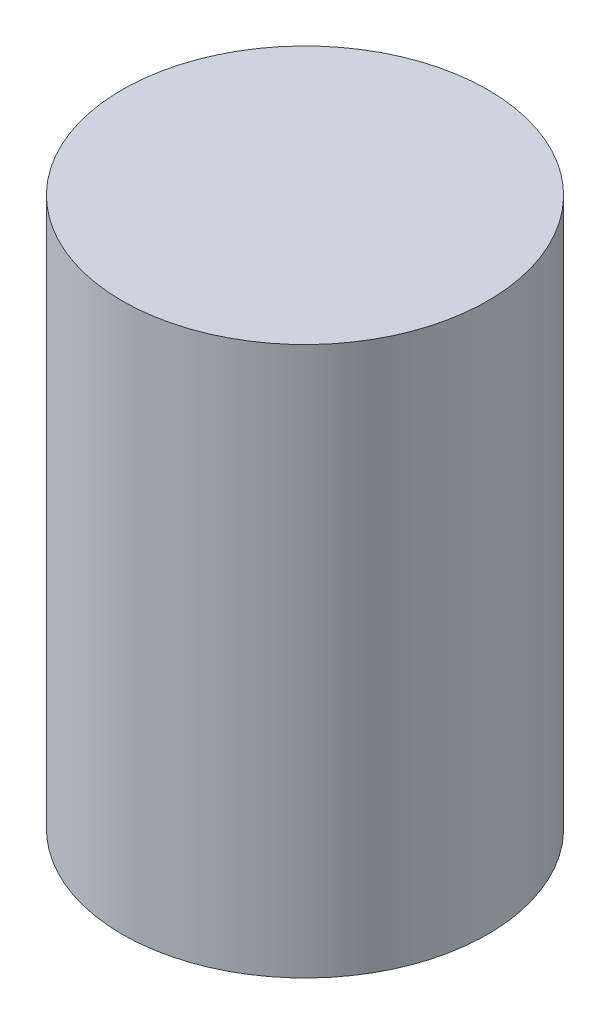
SolidWorks part; units mm, degrees
ref_plane "前视基准面" through (0, 0, 0) normal (0, 0, 1) x (1, 0, 0)
ref_plane "上视基准面" through (0, 0, 0) normal (0, 1, 0) x (1, 0, 0)
ref_plane "右视基准面" through (0, 0, 0) normal (1, 0, 0) x (0, 0, -1)
other "Configuration Table"
sketch "草图1" plane through (0, 0, 0) normal (0, 1, 0) x (1, 0, 0)
  circle A0 centre (0, 0) radius 10
  dimension "D1" = 20
extrude "凸台-拉伸2" add sketch "草图1" along normal blind 30
